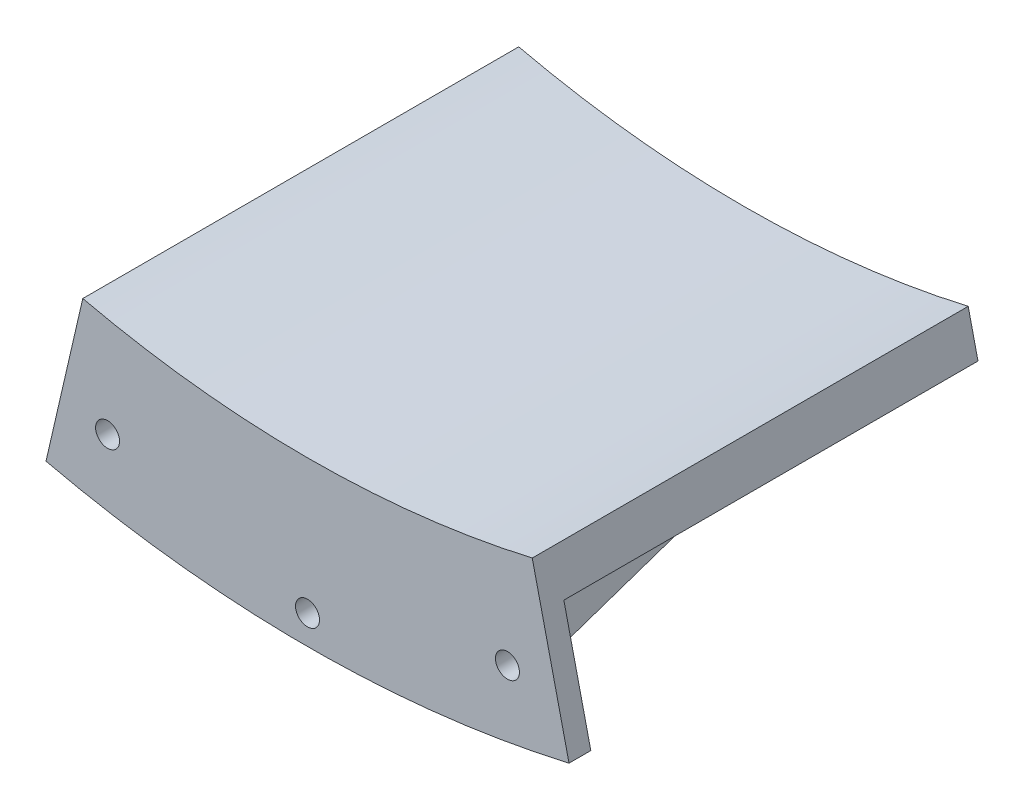
SolidWorks part; units mm, degrees
material "PLA"
ref_plane "前视基准面" through (0, 0, 0) normal (0, 0, 1) x (1, 0, 0)
ref_plane "上视基准面" through (0, 0, 0) normal (0, 1, 0) x (1, 0, 0)
ref_plane "右视基准面" through (0, 0, 0) normal (1, 0, 0) x (0, 0, -1)
sketch "草图1" plane through (0, 0, 0) normal (0, 0, 1) x (1, 0, 0)
  line L0 (0, 226.0354) -> (0, -266.8065) construction
  line L1 (0, 0) -> (-32.2805, -139.8221)
  line L2 (0, 0) -> (32.2805, -139.8221)
  circle A0 centre (0, 0) radius 137.5
  circle A1 centre (0, 0) radius 143.5
  dimension "D1" = 275
  dimension "D2" = 287
  dimension "D3" = 13
extrude "凸台-拉伸1" add sketch "草图1" along normal blind 60 contours A0 L0 A1 L2 | L0 A0 L1 A1
sketch "草图2" plane through (0, 0, 60) normal (0, 0, 1) x (1, 0, 0)
  line L0 (0, 0) -> (35.9922, -155.8992)
  line L1 (0, 0) -> (-35.9922, -155.8992)
  line L2 (-30.9308, -133.9759) -> (-32.2805, -139.8221) construction
  line L3 (30.9308, -133.9759) -> (32.2805, -139.8221) construction
  circle A0 centre (0, 0) radius 160
  arc M6 (-32.2805, -139.8221) -> (32.2805, -139.8221) centre (0, 0) ccw
  dimension "D1" = 320
extrude "凸台-拉伸2" add sketch "草图2" against normal blind 3 contours L1 A0 L0 M6
sketch "草图3" plane through (0, 0, 57) normal (0, 0, -1) x (-1, 0, 0)
  line L0 (0, 0) -> (0, -162.5) construction
  line L1 (0, 0) -> (-16.4216, -161.6681)
  line L2 (0, 0) -> (-22.6156, -160.9186)
  line L3 (0, 0) -> (16.4216, -161.6681)
  line L4 (0, 0) -> (22.6156, -160.9186)
  line L5 (0, 0) -> (-29.6133, -159.7789) construction
  circle A0 centre (0, 0) radius 143.5
  circle A1 centre (0, 0) radius 162.5
  circle A2 centre (0, -156) radius 1.65
  circle A3 centre (0, 0) radius 151 construction
  circle A4 centre (-27.5176, -148.4715) radius 1.65
  circle A5 centre (27.5176, -148.4715) radius 1.65
  arc M9 (32.2805, -139.8221) -> (-32.2805, -139.8221) centre (0, 0) cw
  arc M11 (-35.9922, -155.8992) -> (35.9922, -155.8992) centre (0, 0) ccw
  dimension "D1" = 5.8
  dimension "D3" = 3.3
  dimension "D5" = 302
  dimension "D7" = 3.3
  dimension "D2" = 8
  dimension "D4" = 156
  dimension "D6" = 10.5
extrude "凸台-拉伸3" add sketch "草图3" along normal blind 57 contours A4 | A2 | L2 L1 M9 M11 | L4 L3 M9 M11 | A5
sketch "草图4" plane through (0, 0, 0) normal (0, 0, -1) x (-1, 0, 0)
  circle A0 centre (-27.5176, -148.4715) radius 1.65
  circle A1 centre (0, -156) radius 1.65
  circle A2 centre (27.5176, -148.4715) radius 1.65
  dimension "D1" = 3.3
  dimension "D2" = 3.3
  dimension "D3" = 3.3
extrude "切除-拉伸1" cut sketch "草图4" against normal through all
sketch "草图6" plane through (0, 0, 0) normal (0.9903, 0.1392, 0) x (0, 0, -1)
  line L0 (0, -143.5) -> (-57, -160)
  line L1 (-57, -160) -> (0, -160)
  line L2 (0, -160) -> (0, -143.5)
revolve "切除-旋转1" cut sketch "草图6" angle 360 about axis through (0, 0, 60) along (0, 0, -1)
